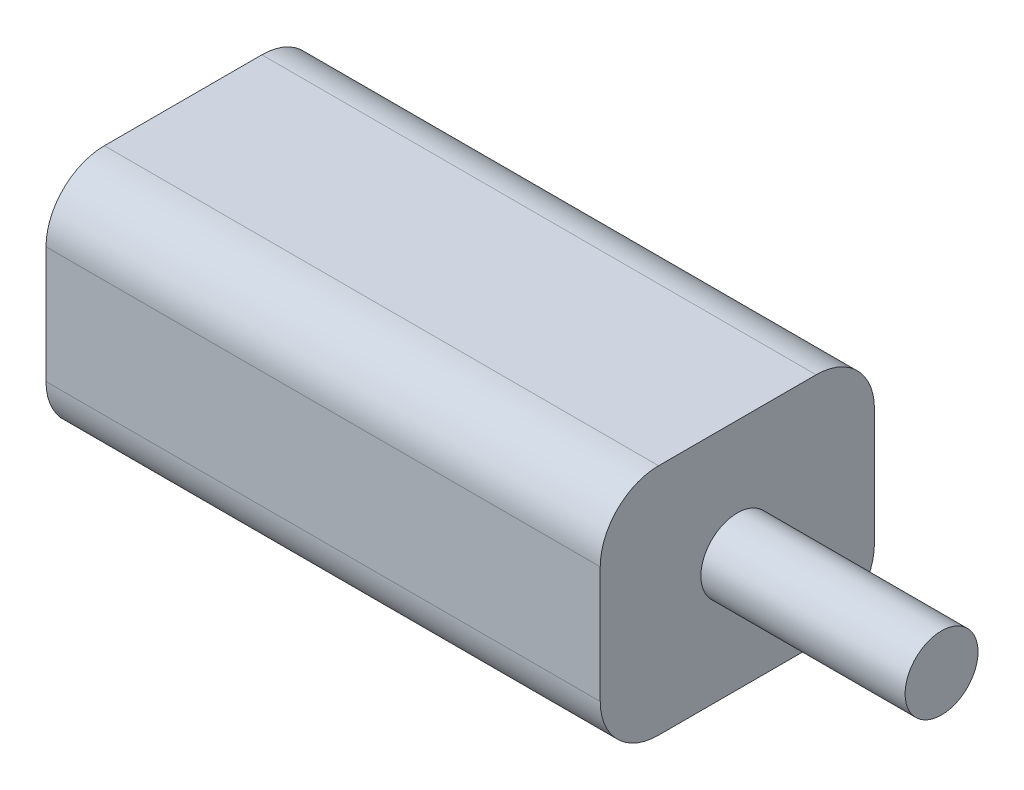
SolidWorks part; units mm, degrees
ref_plane "Front Plane" through (0, 0, 0) normal (0, 0, 1) x (1, 0, 0)
ref_plane "Top Plane" through (0, 0, 0) normal (0, 1, 0) x (1, 0, 0)
ref_plane "Right Plane" through (0, 0, 0) normal (1, 0, 0) x (0, 0, -1)
sketch "Sketch1" plane through (0, 0, 0) normal (1, 0, 0) x (0, 0, -1)
  line L1 (-5.969, 5.08) -> (5.969, 5.08)
  line L2 (-5.969, 5.08) -> (-5.969, -5.08)
  line L3 (-5.969, -5.08) -> (5.969, -5.08)
  line L4 (5.969, 5.08) -> (5.969, -5.08)
  line L5 (-5.969, 5.08) -> (5.969, -5.08) construction
  line L6 (-5.969, -5.08) -> (5.969, 5.08) construction
  point P0 (0, 0)
  dimension "D1" = 10.16
  dimension "D2" = 11.938
extrude "Boss-Extrude1" add sketch "Sketch1" along normal blind 24.13 contours L2 L3 L4 L1
sketch "Sketch2" plane through (24.13, 0, 0) normal (1, 0, 0) x (0, 0, -1)
  circle A0 centre (0, 0) radius 1.5875
  dimension "D1" = 3.175
extrude "Boss-Extrude2" add sketch "Sketch2" along normal blind 8.89 contours A0
fillet "Fillet1" radius 2.54 4 edges at (12.065, -5.08, -5.969) (12.065, 5.08, -5.969) (12.065, -5.08, 5.969) (12.065, 5.08, 5.969)
